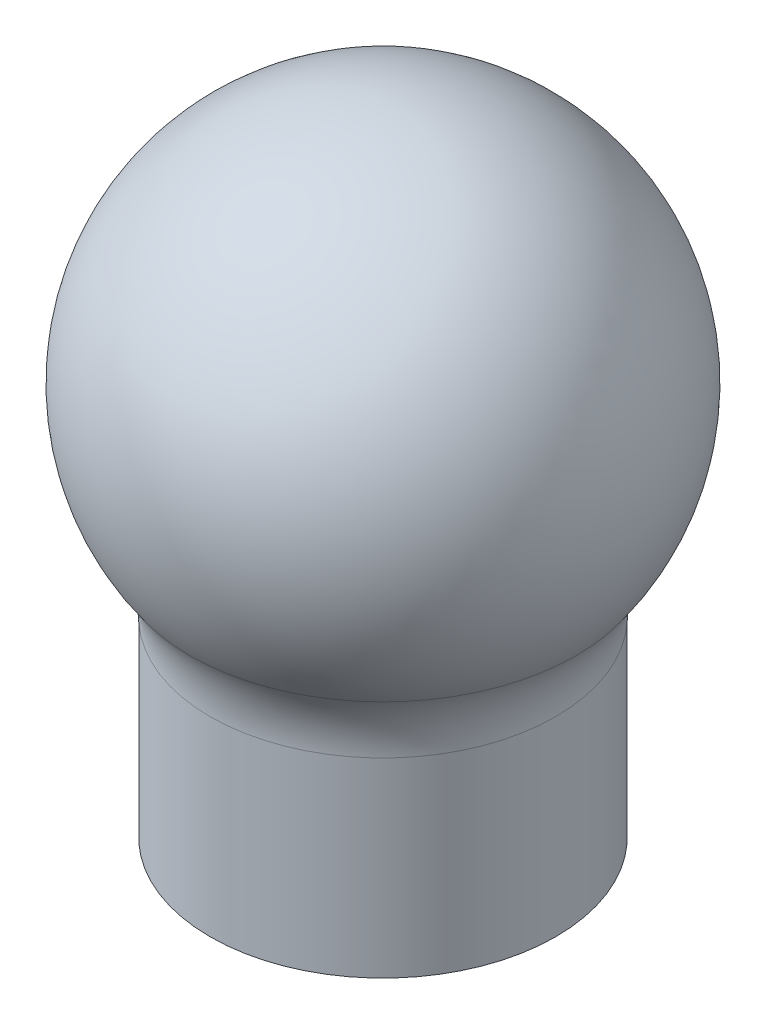
SolidWorks part; units mm, degrees
other "Markup1"
sketch "Sketch4" plane through (-40, 0, 40) normal (0, 0, 1) x (1, 0, 0)
ref_plane "Front Plane" through (0, 0, 0) normal (0, 0, 1) x (1, 0, 0)
ref_plane "Top Plane" through (0, 0, 0) normal (0, 1, 0) x (1, 0, 0)
ref_plane "Right Plane" through (0, 0, 0) normal (1, 0, 0) x (0, 0, -1)
sketch "Sketch1" plane through (0, 0, 0) normal (0, 1, 0) x (1, 0, 0)
  circle A0 centre (0, 0) radius 29
  dimension "D1" = 58
extrude "Boss-Extrude1" add sketch "Sketch1" along normal blind 32
sketch "Sketch2" plane through (0, 0, 0) normal (0, 0, 1) x (1, 0, 0)
  line L0 (0, 0) -> (0, 66) construction
  line L1 (-29, 32) -> (-29, 0) construction
  line L2 (29, 32) -> (-29, 32) construction
  line L3 (0, 66) -> (0, 106) construction
  line L4 (-29, 32) -> (0, 32)
  line L5 (0, 32) -> (0, 106)
  arc A0 (0, 106) -> (-32.4197, 42.5701) centre (0, 66) ccw
  arc A1 (-32.4197, 42.5701) -> (-29, 32) centre (-47.0455, 32) cw
  dimension "D1" = 80
  dimension "D2" = 34
revolve "Revolve1" add sketch "Sketch2" angle 360 about L5
sketch "Sketch3" plane through (0, 0, 0) normal (1, 0, 0) x (0, 0, -1)
  line L0 (0, 106) -> (0, 0) construction
  arc A0 (32.4197, 42.5701) -> (-32.4197, 42.5701) centre (0, 66) ccw construction
